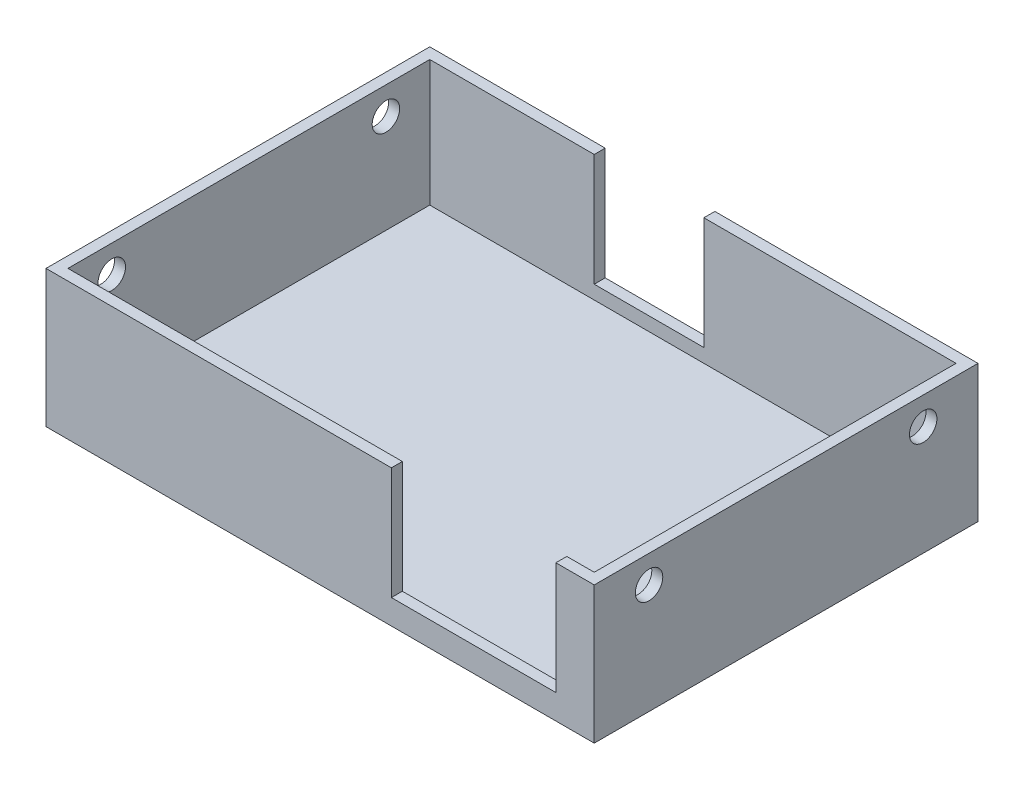
SolidWorks part; units mm, degrees
ref_plane "Front Plane" through (0, 0, 0) normal (0, 0, 1) x (1, 0, 0)
ref_plane "Top Plane" through (0, 0, 0) normal (0, 1, 0) x (1, 0, 0)
ref_plane "Right Plane" through (0, 0, 0) normal (1, 0, 0) x (0, 0, -1)
sketch "Sketch1" plane through (0, 0, 0) normal (0, 1, 0) x (1, 0, 0)
  line L1 (0, 0) -> (127, 0)
  line L2 (0, 0) -> (0, 88.9)
  line L3 (0, 88.9) -> (127, 88.9)
  line L4 (127, 0) -> (127, 88.9)
  dimension "D1" = 127
  dimension "D2" = 88.9
extrude "Boss-Extrude1" add sketch "Sketch1" along normal blind 31.75
shell "Shell1" thickness 2.54
sketch "Sketch3" plane through (127, 0, 0) normal (1, 0, 0) x (0, 0, -1)
  line L0 (0, 31.75) -> (88.9, 31.75) construction
  line L1 (0, 31.75) -> (0, 0) construction
  line L2 (88.9, 31.75) -> (88.9, 0) construction
  circle A0 centre (12.7, 25.4) radius 3.175
  circle A1 centre (76.2, 25.4) radius 3.175
  dimension "D1" = 6.35
  dimension "D6" = 6.35
  dimension "D2" = 6.35
  dimension "D3" = 12.7
  dimension "D4" = 6.35
  dimension "D5" = 12.7
extrude "Cut-Extrude2" cut sketch "Sketch3" against normal blind 31.75
ref_plane "Plane2" through (63.5, 0, 0) normal (1, 0, 0) x (0, 0, -1)
mirror "Mirror2" about plane through (63.5, 0, 0) normal (1, 0, 0) of "Cut-Extrude2"
sketch "Sketch4" plane through (0, 0, 0) normal (0, 0, 1) x (1, 0, 0)
  line L1 (80.01, 31.75) -> (118.11, 31.75)
  line L2 (80.01, 31.75) -> (80.01, 5.715)
  line L3 (80.01, 5.715) -> (118.11, 5.715)
  line L4 (118.11, 31.75) -> (118.11, 5.715)
  line L5 (0, 31.75) -> (127, 31.75) construction
  line L6 (124.46, 31.75) -> (124.46, 2.54) construction
  line L7 (2.54, 2.54) -> (124.46, 2.54) construction
  dimension "D1" = 38.1
  dimension "D2" = 3.175
  dimension "D3" = 6.35
extrude "Cut-Extrude3" cut sketch "Sketch4" against normal blind 31.75
sketch "Sketch5" plane through (0, 0, -88.9) normal (0, 0, -1) x (-1, 0, 0)
  line L1 (-66.04, 31.75) -> (-40.64, 31.75)
  line L2 (-66.04, 31.75) -> (-66.04, 5.715)
  line L3 (-66.04, 5.715) -> (-40.64, 5.715)
  line L4 (-40.64, 31.75) -> (-40.64, 5.715)
  line L6 (-2.54, 31.75) -> (-2.54, 2.54) construction
  line L7 (-127, 31.75) -> (0, 31.75) construction
  line L8 (-124.46, 2.54) -> (-2.54, 2.54) construction
  dimension "D1" = 25.4
  dimension "D2" = 38.1
  dimension "D3" = 3.175
extrude "Cut-Extrude4" cut sketch "Sketch5" against normal blind 31.75
